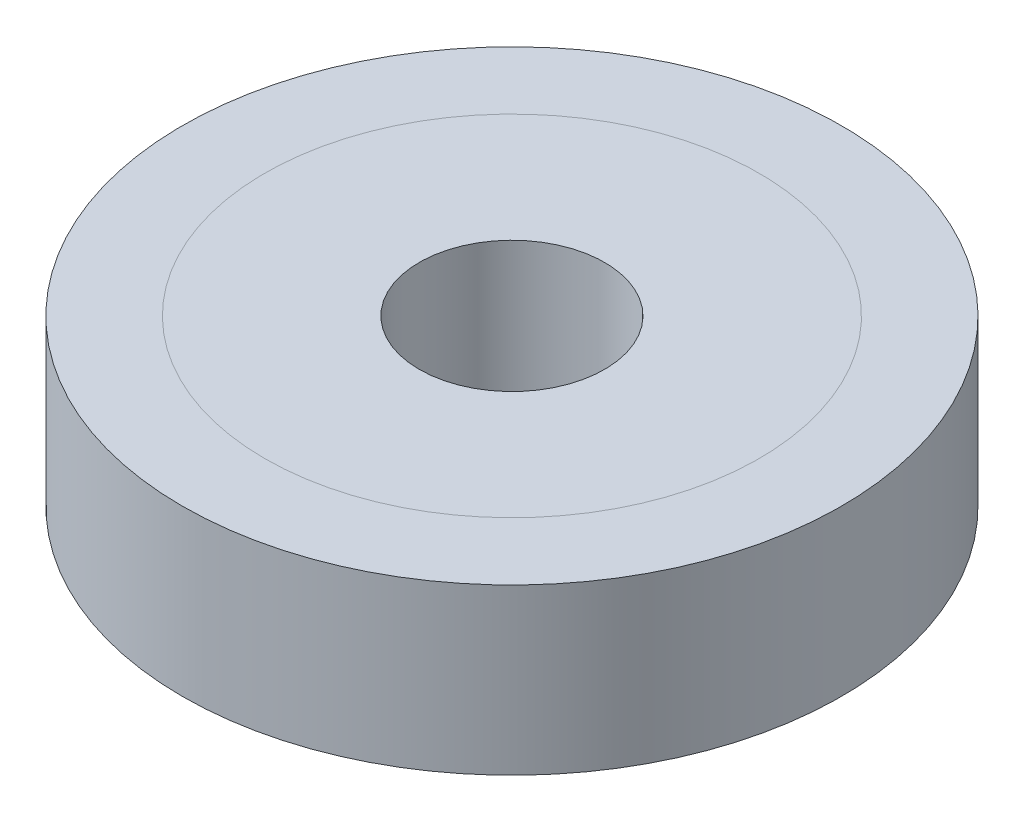
SolidWorks part; units mm, degrees
ref_plane "前视基准面" through (0, 0, 0) normal (0, 0, 1) x (1, 0, 0)
ref_plane "上视基准面" through (0, 0, 0) normal (0, 1, 0) x (1, 0, 0)
ref_plane "右视基准面" through (0, 0, 0) normal (1, 0, 0) x (0, 0, -1)
other "Configuration Table"
sketch "草图1" plane through (0, 0, 0) normal (0, 1, 0) x (1, 0, 0)
  circle A0 centre (0, 0) radius 4.5
  circle A1 centre (0, 0) radius 12
  point P5 (-1.118, 0.8156)
  point P6 (-1.2118, 0.6938)
  dimension "D1" = 9
  dimension "D3" = 24
extrude "凸台-拉伸1" add sketch "草图1" along normal blind 8
sketch "草图2" plane through (0, 8, 0) normal (0, 1, 0) x (1, 0, 0)
  circle A0 centre (0, 0) radius 16
  circle A1 centre (0, 0) radius 12
  circle A2 centre (0, 0) radius 12
  dimension "D1" = 0
  dimension "D2" = 4
extrude "凸台-拉伸2" add sketch "草图2" against normal up to surface (8 mm away) separate body up to face at (0, 0, 12)
